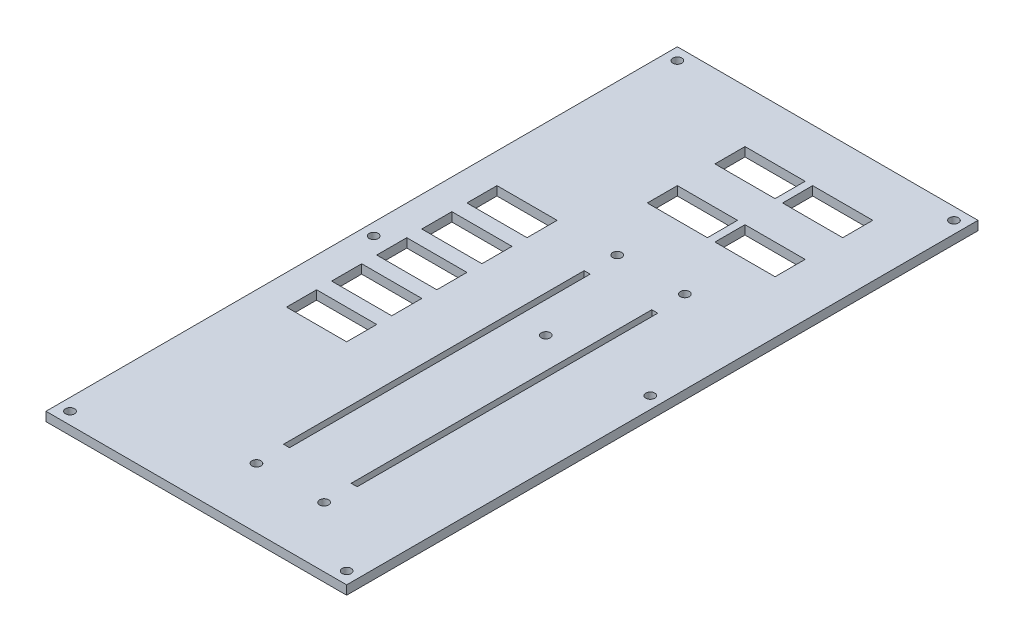
SolidWorks part; units mm, degrees
ref_plane "Front Plane" through (0, 0, 0) normal (0, 0, 1) x (1, 0, 0)
ref_plane "Top Plane" through (0, 0, 0) normal (0, 1, 0) x (1, 0, 0)
ref_plane "Right Plane" through (0, 0, 0) normal (1, 0, 0) x (0, 0, -1)
sketch "Sketch1" plane through (0, 0, 0) normal (0, 1, 0) x (1, 0, 0)
  line L1 (-50, -105) -> (50, -105)
  line L2 (-50, -105) -> (-50, 105)
  line L3 (-50, 105) -> (50, 105)
  line L4 (50, -105) -> (50, 105)
  line L5 (-50, -105) -> (50, 105) construction
  line L6 (-50, 105) -> (50, -105) construction
  point P0 (0, 0)
  point P24 (0, 0)
  point P25 (0, 0)
  point P26 (0, 0)
  point P27 (0, 0)
  point P28 (0, 0)
  dimension "D1" = 210
  dimension "D2" = 100
extrude "Boss-Extrude1" add sketch "Sketch1" along normal blind 3 contours L2 L3 L4 L1
sketch "Sketch3" plane through (0, 3, 0) normal (0, 1, 0) x (1, 0, 0)
  line L0 (-1, 25) -> (1, 25)
  line L1 (-1, 25) -> (-1, -75)
  line L2 (-1, -75) -> (1, -75)
  line L3 (1, 25) -> (1, -75)
  line L4 (-1, 25) -> (1, -75) construction
  line L5 (-1, -75) -> (1, 25) construction
  line L6 (-50, -105) -> (-50, 105) construction
  circle A0 centre (0, -85) radius 1.5
  circle A1 centre (0, 35) radius 1.5
  point P0 (0, -25)
  point P9 (0, 0)
  point P13 (0, -14.4645)
  dimension "D3" = 3
  dimension "D4" = 3
  dimension "D1" = 100
  dimension "D2" = 2
  dimension "D5" = 120
  dimension "D6" = 60
  dimension "D7" = 50
  dimension "D8" = 25
extrude "Cut-Extrude1" cut sketch "Sketch3" against normal up to next
pattern_linear "LPattern1" count 2 spacing 22.5 along (1, 0, 0) of "Cut-Extrude1"
sketch "Sketch4" plane through (0, 3, 0) normal (0, 1, 0) x (1, 0, 0)
  line L1 (-10, 55) -> (10, 55)
  line L2 (-10, 55) -> (-10, 65)
  line L3 (-10, 65) -> (10, 65)
  line L4 (10, 55) -> (10, 65)
  line L5 (-10, 55) -> (10, 65) construction
  line L6 (-10, 65) -> (10, 55) construction
  circle A0 centre (0, 35) radius 1.5 construction
  point P0 (0, 60)
  point P5 (0, 0)
  dimension "D1" = 10
  dimension "D2" = 20
  dimension "D3" = 25
extrude "Cut-Extrude2" cut sketch "Sketch4" against normal up to next
pattern_linear "LPattern2" count 2 spacing 22.5 along (1, 0, 0) count 2 spacing 22.5 along (0, 0, -1) of "Cut-Extrude2"
sketch "Sketch5" plane through (0, 3, 0) normal (0, 1, 0) x (1, 0, 0)
  line L0 (-50, 105) -> (50, 105) construction
  line L1 (-50, -105) -> (-50, 105) construction
  line L2 (50, -105) -> (50, 105) construction
  line L3 (-50, -105) -> (50, -105) construction
  circle A0 centre (-46, 101) radius 1.5
  circle A1 centre (46, 101) radius 1.5
  circle A2 centre (46, -101) radius 1.5
  circle A3 centre (-46, -101) radius 1.5
  circle A4 centre (11.25, 0) radius 1.5
  point P16 (0, 0)
  dimension "D1" = 3
  dimension "D4" = 3
  dimension "D9" = 3
  dimension "D10" = 3
  dimension "D13" = 3
  dimension "D2" = 4
  dimension "D3" = 4
  dimension "D5" = 4
  dimension "D6" = 4
  dimension "D7" = 4
  dimension "D8" = 4
  dimension "D11" = 4
  dimension "D12" = 4
  dimension "D14" = 11.25
extrude "Cut-Extrude3" cut sketch "Sketch5" against normal up to next
sketch "Sketch6" plane through (0, 3, 0) normal (0, 1, 0) x (1, 0, 0)
  line L0 (-50, -105) -> (-50, 105) construction
  line L1 (-40, 35) -> (-20, 35)
  line L2 (-40, 35) -> (-40, 25)
  line L3 (-40, 25) -> (-20, 25)
  line L4 (-20, 35) -> (-20, 25)
  line L5 (-40, 35) -> (-20, 25) construction
  line L6 (-40, 25) -> (-20, 35) construction
  point P0 (-30, 30)
  dimension "D1" = 20
  dimension "D2" = 10
  dimension "D3" = 20
  dimension "D4" = 30
extrude "Cut-Extrude4" cut sketch "Sketch6" against normal up to next
pattern_linear "LPattern3" count 5 spacing 15 along (0, 0, 1) of "Cut-Extrude4"
sketch "Sketch7" plane through (0, 3, 0) normal (0, 1, 0) x (1, 0, 0)
  line L0 (-50, -105) -> (-50, 105) construction
  circle A0 centre (-46, 0) radius 1.5
  point P4 (0, 0)
  dimension "D1" = 3
  dimension "D2" = 4
extrude "Cut-Extrude5" cut sketch "Sketch7" against normal up to next
sketch "Sketch8" plane through (0, 3, 0) normal (0, 1, 0) x (1, 0, 0)
  line L0 (50, -105) -> (50, 105) construction
  circle A0 centre (46, 0) radius 1.5
  point P4 (0, 0)
  dimension "D1" = 3
  dimension "D2" = 4
extrude "Cut-Extrude6" cut sketch "Sketch8" against normal up to next
